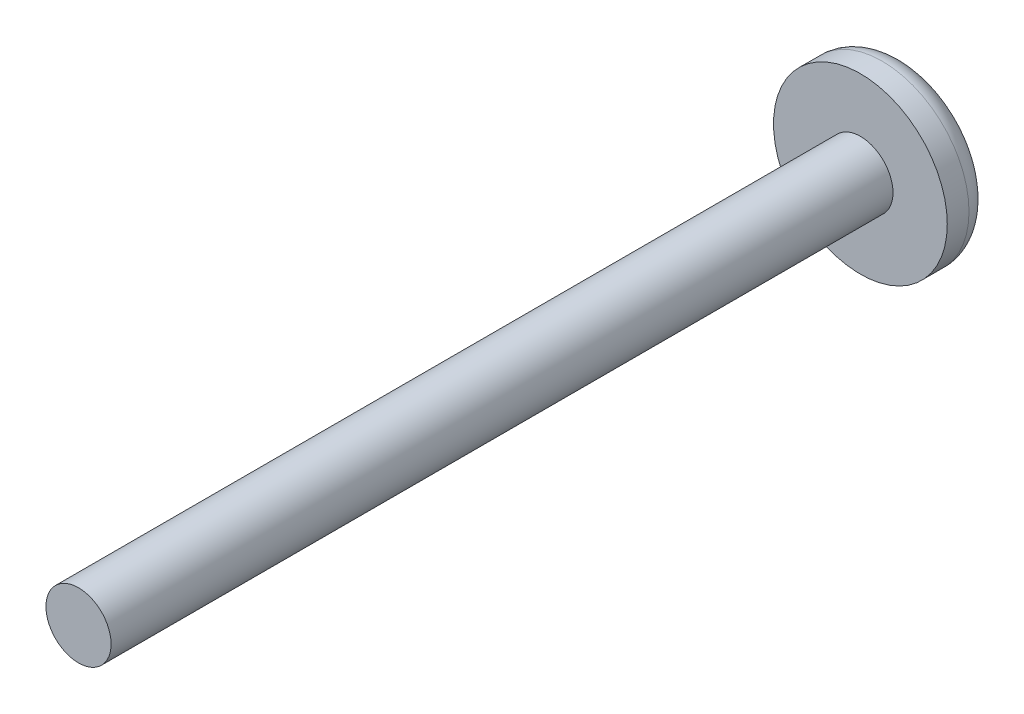
SolidWorks part; units mm, degrees
ref_plane "Front Plane" through (0, 0, 0) normal (0, 0, 1) x (1, 0, 0)
ref_plane "Top Plane" through (0, 0, 0) normal (0, 1, 0) x (1, 0, 0)
ref_plane "Right Plane" through (0, 0, 0) normal (1, 0, 0) x (0, 0, -1)
sketch "Sketch1" plane through (0, 0, 0) normal (0, 1, 0) x (1, 0, 0)
  line L0 (0, 0) -> (0, 38)
  line L1 (0, 0) -> (1.5, 0)
  line L4 (1.5, 0) -> (1.5, 36)
  line L5 (0, 38) -> (4, 38)
  line L7 (1.5, 36) -> (4, 36)
  line L8 (4, 38) -> (4, 36)
  dimension "D1" = 4
  dimension "D2" = 38
  dimension "D3" = 2
  dimension "D4" = 1.5
revolve "Revolve1" add sketch "Sketch1" angle 360 about L0
fillet "Fillet1" radius 1 1 edges at (4, 0, -38)
